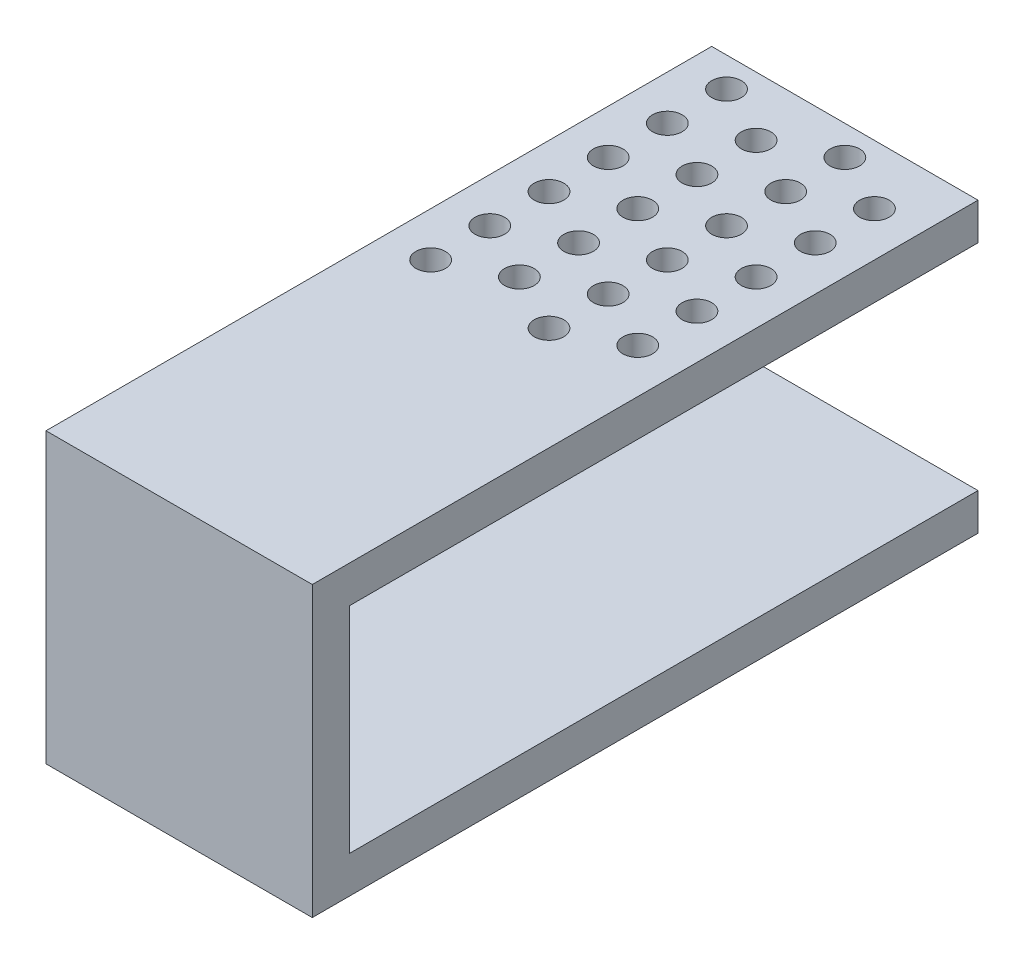
SolidWorks part; units mm, degrees
ref_plane "Front Plane" through (0, 0, 0) normal (0, 0, 1) x (1, 0, 0)
ref_plane "Top Plane" through (0, 0, 0) normal (0, 1, 0) x (1, 0, 0)
ref_plane "Right Plane" through (0, 0, 0) normal (1, 0, 0) x (0, 0, -1)
sketch "Sketch2" plane through (0, 0, 0) normal (0, 1, 0) x (1, 0, 0)
  line L1 (-20, 16) -> (-2, 16)
  line L2 (-20, 16) -> (-20, -8)
  line L3 (-20, -8) -> (-2, -8)
  line L4 (-2, 16) -> (-2, -8)
  circle A0 centre (-17, -6) radius 1
  circle A1 centre (-17, -2) radius 1
  circle A2 centre (-17, 2) radius 1
  circle A3 centre (-17, 6) radius 1
  circle A4 centre (-17, 10) radius 1
  circle A5 centre (-17, 14) radius 1
  circle A6 centre (-13, -4) radius 1
  circle A7 centre (-13, 0) radius 1
  circle A8 centre (-13, 4) radius 1
  circle A9 centre (-13, 8) radius 1
  circle A10 centre (-13, 12) radius 1
  circle A11 centre (-9, -6) radius 1
  circle A12 centre (-9, -2) radius 1
  circle A13 centre (-9, 2) radius 1
  circle A14 centre (-9, 6) radius 1
  circle A15 centre (-9, 10) radius 1
  circle A16 centre (-9, 14) radius 1
  circle A17 centre (-5, -4) radius 1
  circle A18 centre (-5, 0) radius 1
  circle A19 centre (-5, 4) radius 1
  circle A20 centre (-5, 8) radius 1
  circle A21 centre (-5, 12) radius 1
  dimension "D1" = 24
  dimension "D2" = 18
extrude "Boss-Extrude2" add sketch "Sketch2" along normal blind 2.5
sketch "Sketch3" plane through (0, 0, 8) normal (0, 0, 1) x (1, 0, 0)
  line L1 (-20, 2.5) -> (-2, 2.5)
  line L2 (-20, 2.5) -> (-20, 0)
  line L3 (-20, 0) -> (-2, 0)
  line L4 (-2, 2.5) -> (-2, 0)
extrude "Boss-Extrude3" add sketch "Sketch3" along normal blind 21
sketch "Sketch4" plane through (0, 0, 0) normal (0, -1, 0) x (-1, 0, 0)
  line L0 (20, 16) -> (20, -29) construction
  line L1 (2, -29) -> (20, -29)
  line L2 (2, -29) -> (2, -26.5)
  line L3 (2, -26.5) -> (20, -26.5)
  line L4 (20, -29) -> (20, -26.5)
  dimension "D1" = 2.5
extrude "Boss-Extrude4" add sketch "Sketch4" along normal blind 17
sketch "Sketch5" plane through (0, 0, 26.5) normal (0, 0, -1) x (-1, 0, 0)
  line L0 (20, -17) -> (20, 0) construction
  line L1 (2, -17) -> (20, -17)
  line L2 (2, -17) -> (2, -14.5)
  line L3 (2, -14.5) -> (20, -14.5)
  line L4 (20, -17) -> (20, -14.5)
  dimension "D1" = 2.5
extrude "Boss-Extrude5" add sketch "Sketch5" along normal blind 42.5
